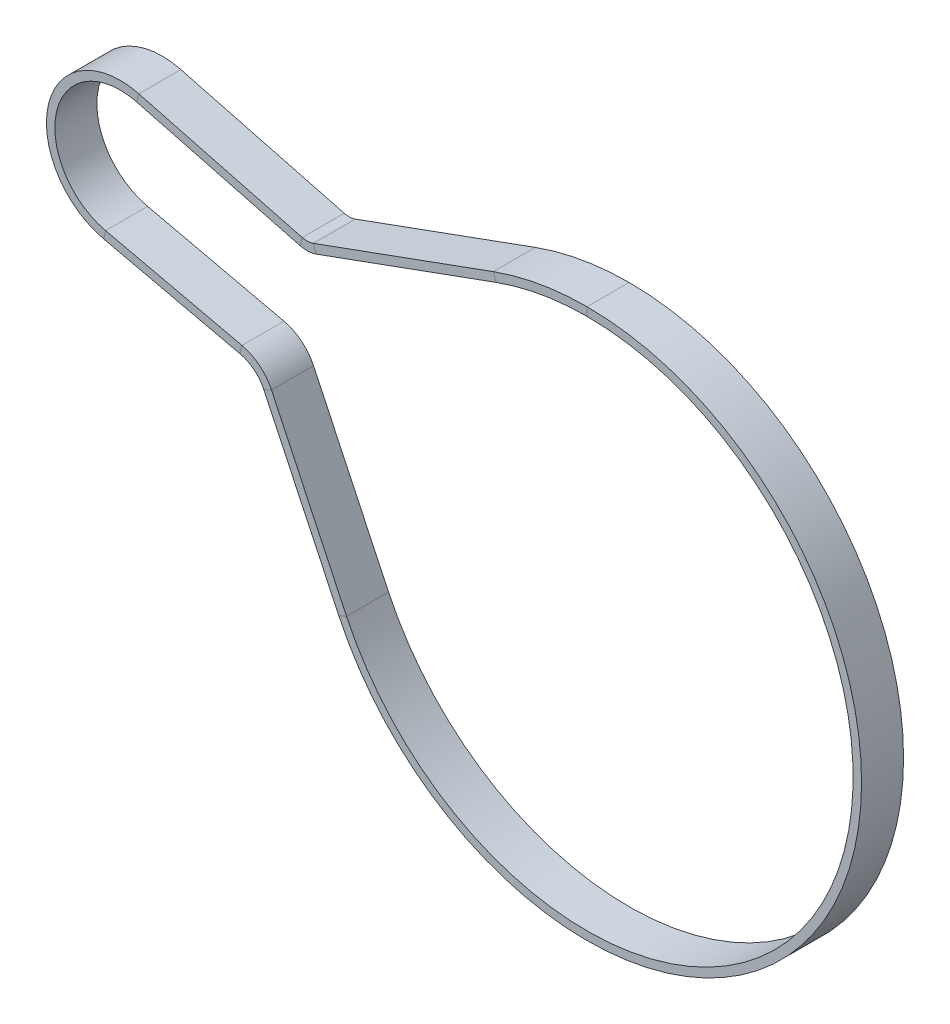
SolidWorks part; units mm, degrees
ref_plane "前视基准面" through (0, 0, 0) normal (0, 0, 1) x (1, 0, 0)
ref_plane "上视基准面" through (0, 0, 0) normal (0, 1, 0) x (1, 0, 0)
ref_plane "右视基准面" through (0, 0, 0) normal (1, 0, 0) x (0, 0, -1)
sketch "Sketch2" plane through (0, 0, 0) normal (0, 0, 1) x (1, 0, 0)
  line L0 (0, 0) -> (1, 0) construction
  line L1 (0, 0) -> (0, 1) construction
  line L2 (-19.4855, 53.566) -> (-58.0173, 39.5494)
  line L3 (-61.4682, 39.3889) -> (-96.456, 48.544)
  line L7 (-103.1299, 21.3544) -> (-73.9208, 14.6546)
  line L8 (-67.5943, 9.5692) -> (-51.5189, -24.3887)
  arc A0 (-51.5189, -24.3887) -> (-19.4855, 53.566) centre (0, 0) ccw
  arc A1 (-58.0173, 39.5494) -> (-61.4682, 39.3889) centre (-60, 45) cw
  arc A2 (-96.456, 48.544) -> (-103.1299, 21.3544) centre (-100, 35) ccw
  arc A4 (-73.9208, 14.6546) -> (-67.5943, 9.5692) centre (-76, 5.59) cw
sketch "Sketch3" plane through (0, 0, 0) normal (1, 0, 0) x (0, 0, -1)
  line L0 (-4.5, 57) -> (4.5, 57)
  line L1 (4.5, 58.8) -> (-4.5, 58.8)
  line L2 (-4.5, 58.8) -> (-4.5, 57)
  line L5 (0, 57) -> (0, -57) construction
  line L6 (4.5, 58.8) -> (4.5, 57)
  dimension "D1" = 9
  dimension "D2" = 57
  dimension "D3" = 4.5
  dimension "D4" = 1.8
sweep "Sweep1" add profiles "Sketch3" path "Sketch2"
